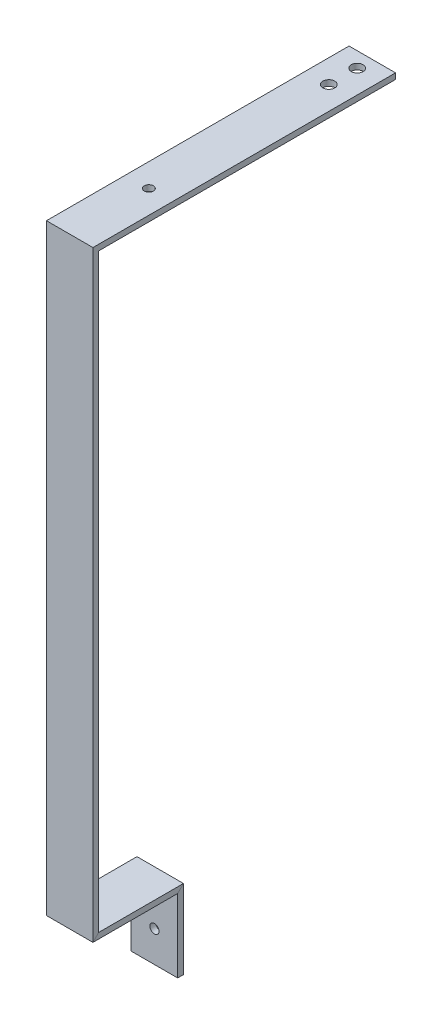
SolidWorks part; units mm, degrees
ref_plane "Alzado" through (0, 0, 0) normal (0, 0, 1) x (1, 0, 0)
ref_plane "Planta" through (0, 0, 0) normal (0, 1, 0) x (1, 0, 0)
ref_plane "Vista lateral" through (0, 0, 0) normal (1, 0, 0) x (0, 0, -1)
sketch "Croquis1" plane through (0, 0, 0) normal (0, 0, 1) x (1, 0, 0)
  line L1 (-25.4, 3.155) -> (25.4, 3.155)
  line L2 (-25.4, 3.155) -> (-25.4, -3.155)
  line L3 (-25.4, -3.155) -> (25.4, -3.155)
  line L4 (25.4, 3.155) -> (25.4, -3.155)
  line L5 (-25.4, 3.155) -> (25.4, -3.155) construction
  line L6 (-25.4, -3.155) -> (25.4, 3.155) construction
  point P0 (0, 0)
  dimension "D1" = 50.8
  dimension "D2" = 6.31
extrude "Saliente-Extruir1" add sketch "Croquis1" along normal blind 330.7
sketch "Croquis3" plane through (0, -3.155, 0) normal (0, -1, 0) x (1, 0, 0)
  line L1 (25.4, 324.39) -> (-25.4, 324.39)
  line L2 (25.4, 324.39) -> (25.4, 330.7)
  line L3 (25.4, 330.7) -> (-25.4, 330.7)
  line L4 (-25.4, 324.39) -> (-25.4, 330.7)
  line L5 (25.4, 324.39) -> (-25.4, 330.7) construction
  line L6 (25.4, 330.7) -> (-25.4, 324.39) construction
  point P0 (0, 327.545)
  dimension "D1" = 6.31
  dimension "D2" = 50.8
extrude "Saliente-Extruir2" add sketch "Croquis3" along normal blind 638.2
sketch "Croquis7" plane through (0, -641.355, 0) normal (0, -1, 0) x (1, 0, 0)
  line L0 (25.4, 324.39) -> (25.4, 330.7)
  line L1 (25.4, 330.7) -> (-25.4, 330.7)
  line L2 (-25.4, 330.7) -> (-25.4, 324.39)
  line L3 (-25.4, 324.39) -> (25.4, 324.39)
  line L4 (0, 324.39) -> (0, 330.7) construction
  line L5 (0, 330.7) -> (0, 327.545) construction
  line L6 (0, 327.545) -> (-7.9034, 327.545) construction
sketch3d "Croquis3D1"
  line L0 (0, -641.355, 327.545) -> (0, -651.355, 327.545)
  line L1 (0, -651.355, 327.545) -> (0, -651.355, 234.935)
  line L2 (0, -651.355, 234.935) -> (0, -734.515, 234.935)
  dimension "D1" = 10
  dimension "D2" = 92.61
  dimension "D3" = 83.16
sweep "Barrer1" add profiles "Croquis7" path "Croquis3D1"
sketch "Croquis8" plane through (0, 0, 231.78) normal (0, 0, -1) x (-1, 0, 0)
  line L0 (-2.7547, -689.1653) -> (0, -700.505) construction
  line L1 (0, -700.505) -> (4.75, -700.505) construction
  line L2 (0, -700.505) -> (0, -734.515) construction
  line L3 (25.4, -734.515) -> (-25.4, -734.515) construction
  circle A0 centre (0, -700.505) radius 5
  dimension "D1" = 10
  dimension "D2" = 34.01
extrude "Cortar-Extruir2" cut sketch "Croquis8" against normal blind 15.875
sketch "Croquis9" plane through (0, 3.155, 0) normal (0, 1, 0) x (1, 0, 0)
  line L0 (0, 0) -> (0, -16.5) construction
  line L1 (0, -16.5) -> (0, -47.5) construction
  circle A0 centre (0, -47.5) radius 6.5
  circle A1 centre (0, -16.5) radius 6.5
  dimension "D1" = 13
  dimension "D2" = 13
extrude "Cortar-Extruir3" cut sketch "Croquis9" against normal blind 15.875
sketch "Croquis11" plane through (0, 3.155, 0) normal (0, 1, 0) x (1, 0, 0)
  line L0 (0, -330.7) -> (0, -244.19) construction
  line L1 (25.4, -330.7) -> (-25.4, -330.7) construction
  circle A0 centre (0, -244.19) radius 5
  dimension "D2" = 10
  dimension "D1" = 86.51
extrude "Cortar-Extruir5" cut sketch "Croquis11" against normal blind 10
